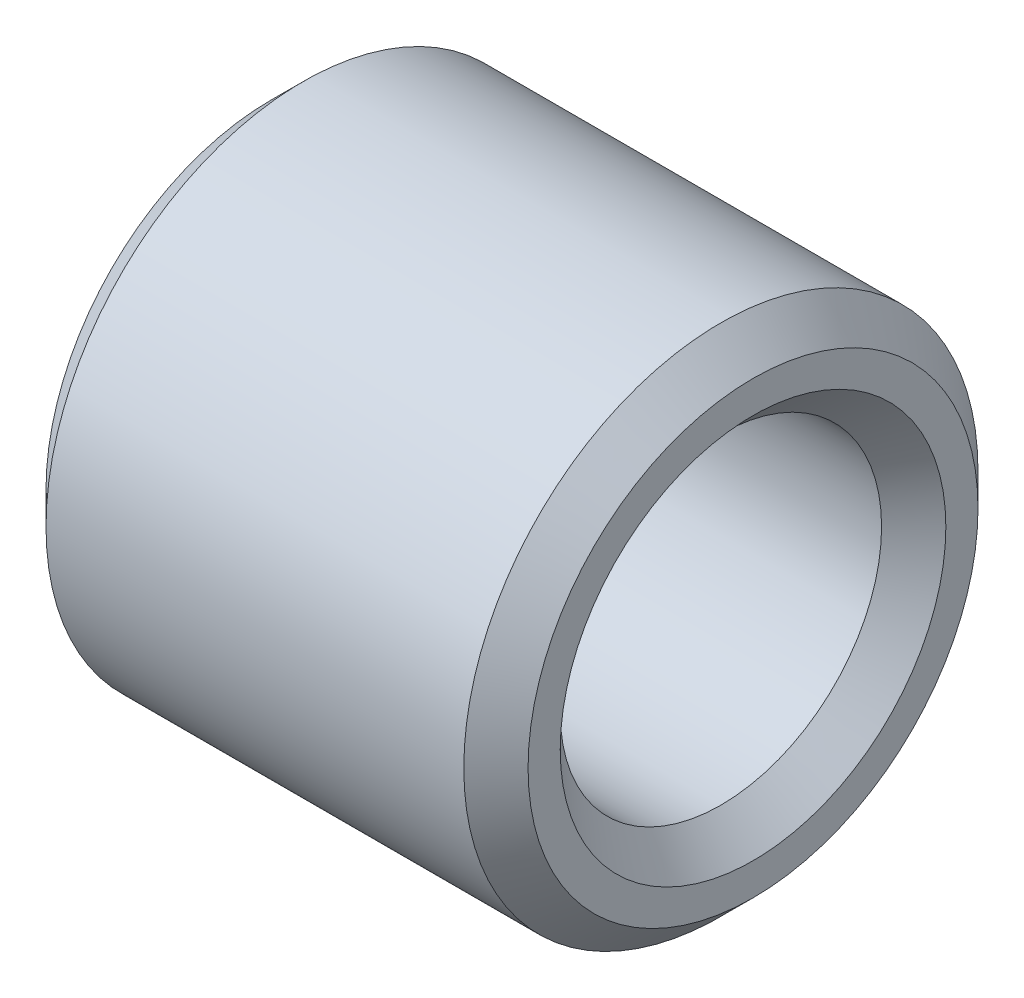
SolidWorks part; units mm, degrees
material "黄铜"
ref_plane "前视基准面" through (0, 0, 0) normal (0, 0, 1) x (1, 0, 0)
ref_plane "上视基准面" through (0, 0, 0) normal (0, 1, 0) x (1, 0, 0)
ref_plane "右视基准面" through (0, 0, 0) normal (1, 0, 0) x (0, 0, -1)
sketch "草图1" plane through (0, 0, 0) normal (1, 0, 0) x (0, 0, -1)
  circle A0 centre (0, 0) radius 2.5
  circle A1 centre (0, 0) radius 4
  dimension "D1" = 5
  dimension "D2" = 8
extrude "凸台-拉伸1" add sketch "草图1" along normal blind 7.5
chamfer "倒角1" distance 0.5 angle 45 4 edges at (0, 0, -4) (0, 0, -2.5) (7.5, 0, -2.5) (7.5, 0, -4)
